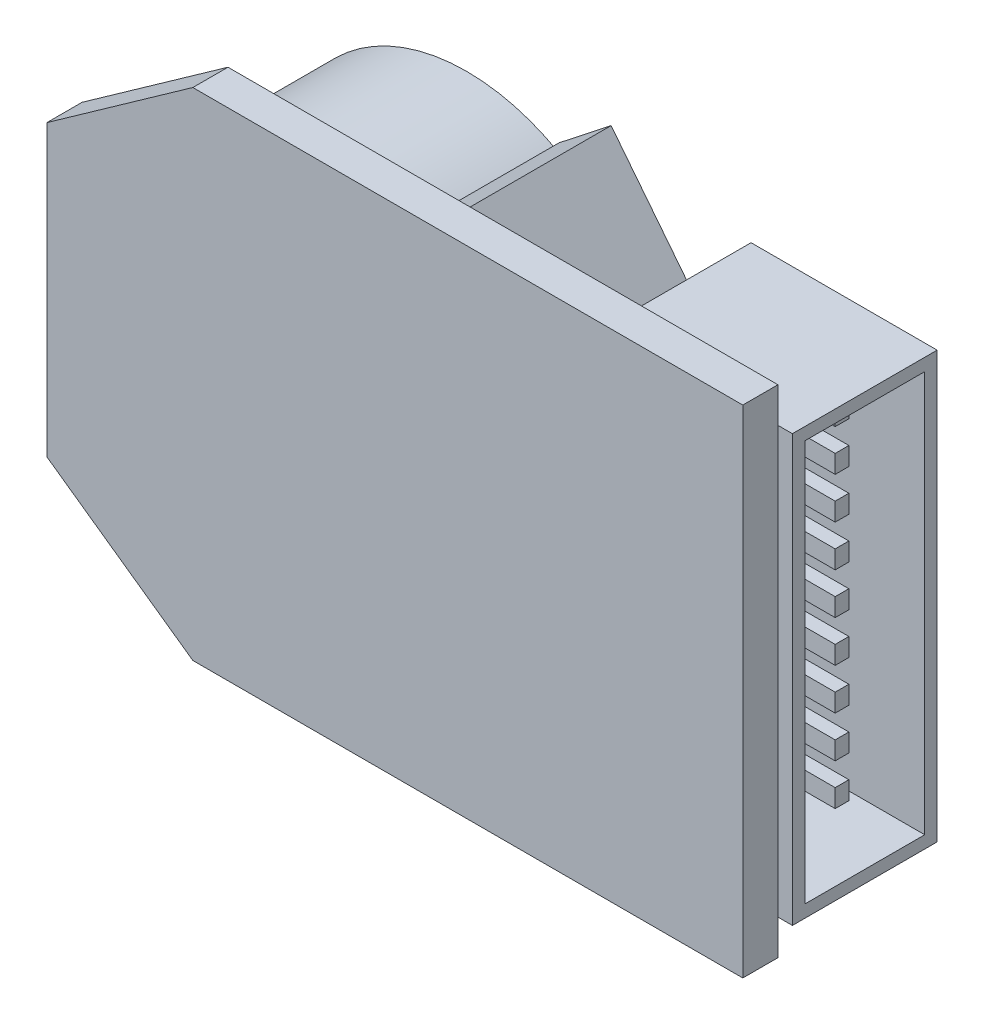
SolidWorks part; units mm, degrees
ref_plane "Alzado" through (0, 0, 0) normal (0, 0, 1) x (1, 0, 0)
ref_plane "Planta" through (0, 0, 0) normal (0, 1, 0) x (1, 0, 0)
ref_plane "Vista lateral" through (0, 0, 0) normal (1, 0, 0) x (0, 0, -1)
sketch "Croquis1" plane through (0, 0, 0) normal (0, 0, 1) x (1, 0, 0)
  line L0 (8.415, 6) -> (-4.885, 6)
  line L1 (-8.415, -6) -> (8.415, -6) construction
  line L2 (-8.415, -6) -> (-8.415, 6) construction
  line L3 (-8.415, 6) -> (8.415, 6) construction
  line L4 (8.415, -6) -> (8.415, 6)
  line L5 (-8.415, -6) -> (8.415, 6) construction
  line L6 (-8.415, 6) -> (8.415, -6) construction
  line L7 (0, 0) -> (-8.415, 0) construction
  line L8 (-8.415, -3.5) -> (-8.415, 3.5)
  line L9 (-8.415, 3.5) -> (-4.885, 6)
  line L10 (-8.415, -3.5) -> (-4.885, -6)
  line L11 (8.415, -6) -> (-4.885, -6)
  point P0 (0, 0)
  dimension "D1" = 16.83
  dimension "D2" = 12
  dimension "D3" = 13.3
  dimension "D4" = 3.5
extrude "Saliente-Extruir1" add sketch "Croquis1" along normal blind 0.85
ref_plane "Plano1" through (0, 0, -1) normal (0, 0, -1) x (-1, 0, 0)
sketch "Croquis2" plane through (0, 0, -1) normal (0, 0, -1) x (-1, 0, 0)
  circle A0 centre (3.415, 0) radius 0.85 construction
  circle A1 centre (3.415, 0) radius 0.85 construction
  circle A2 centre (3.415, 0) radius 0.7322
  circle A3 centre (3.415, 0) radius 4.5
  dimension "D1" = 9
extrude "Saliente-Extruir2" add sketch "Croquis2" along normal blind 3.3 separate body
sketch "Croquis3" plane through (0, 0, 0) normal (0, 0, -1) x (-1, 0, 0)
  line L0 (3.415, 0) -> (-1.5379, 3.8934) construction
  line L1 (-1.5379, 3.8934) -> (-2.7739, 2.3211) construction
  line L2 (-1.5379, 3.8934) -> (-0.3019, 5.4658) construction
  line L3 (-2.1668, 4.3878) -> (-0.9308, 5.9602)
  line L4 (-2.1668, 4.3878) -> (-3.4028, 2.8155)
  line L5 (-0.909, 3.399) -> (0.3271, 4.9714)
  line L6 (-0.909, 3.399) -> (-2.145, 1.8267)
  line L7 (-3.4028, 2.8155) -> (-2.145, 1.8267)
  line L8 (-0.9308, 5.9602) -> (0.3271, 4.9714)
  line L9 (3.415, 0) -> (-5.085, 0) construction
  line L10 (-0.9308, -5.9602) -> (0.3271, -4.9714)
  line L11 (-0.909, -3.399) -> (0.3271, -4.9714)
  line L12 (-0.909, -3.399) -> (-2.145, -1.8267)
  line L13 (-3.4028, -2.8155) -> (-2.145, -1.8267)
  line L14 (-2.1668, -4.3878) -> (-3.4028, -2.8155)
  line L15 (-2.1668, -4.3878) -> (-0.9308, -5.9602)
  dimension "D1" = 6.3
  dimension "D2" = 2
  dimension "D3" = 2
  dimension "D4" = 0.8
  dimension "D5" = 0.8
extrude "Saliente-Extruir3" add sketch "Croquis3" along normal blind 3.45
sketch "Croquis4" plane through (0, 0, 0) normal (0, 0, -1) x (-1, 0, 0)
  line L0 (-8.415, -6) -> (-8.415, 6) construction
  line L1 (-8.415, -6) -> (-8.415, 6) construction
  line L2 (-8.415, 0) -> (-4.265, 0) construction
  line L3 (-8.415, 0) -> (-8.765, 0) construction
  line L4 (-4.265, 5.15) -> (-4.265, -5.15)
  line L5 (-4.265, -5.15) -> (-8.765, -5.15)
  line L6 (-8.765, -5.15) -> (-8.765, 5.15)
  line L7 (-4.265, 5.15) -> (-8.765, 5.15)
  dimension "D1" = 4.15
  dimension "D2" = 0.35
  dimension "D3" = 5.15
extrude "Saliente-Extruir4" add sketch "Croquis4" along normal blind 3.5
sketch "Croquis5" plane through (8.765, 0, 0) normal (1, 0, 0) x (0, 0, -1)
  line L8 (0.3, 4.85) -> (0.3, -4.85)
  line L9 (0.3, -4.85) -> (3.2, -4.85)
  line L10 (3.2, -4.85) -> (3.2, 4.85)
  line L11 (3.2, 4.85) -> (0.3, 4.85)
  line L12 (0.3, 4.85) -> (0.3, -4.85)
  line L13 (0.3, -4.85) -> (3.2, -4.85)
  line L14 (3.2, -4.85) -> (3.2, 4.85)
  line L15 (3.2, 4.85) -> (0.3, 4.85)
  dimension "D1" = 0.3
extrude "Cortar-Extruir1" cut sketch "Croquis5" against normal blind 3
sketch "Croquis6" plane through (5.765, 0, 0) normal (1, 0, 0) x (0, 0, -1)
  line L0 (3.2, -4.85) -> (3.2, 4.85) construction
  line L1 (3.2, -4.85) -> (3.2, 4.85) construction
  line L2 (3.2, 0) -> (2.2, 0) construction
  line L3 (2.2, 0) -> (2.2, -3.1595) construction
  line L4 (2.0344, 0.22) -> (2.3656, 0.22)
  line L5 (2.0344, 0.22) -> (2.0344, -0.22)
  line L6 (2.0344, -0.22) -> (2.3656, -0.22)
  line L7 (2.3656, 0.22) -> (2.3656, -0.22)
  line L8 (2.0344, 0.22) -> (2.3656, -0.22) construction
  line L9 (2.0344, -0.22) -> (2.3656, 0.22) construction
  line L10 (2.3656, 1.22) -> (2.3656, 0.78)
  line L11 (2.0344, 1.22) -> (2.3656, 1.22)
  line L12 (2.0344, 1.22) -> (2.0344, 0.78)
  line L13 (2.0344, 0.78) -> (2.3656, 0.78)
  line L14 (2.3656, 2.22) -> (2.3656, 1.78)
  line L15 (2.0344, 2.22) -> (2.3656, 2.22)
  line L16 (2.0344, 2.22) -> (2.0344, 1.78)
  line L17 (2.0344, 1.78) -> (2.3656, 1.78)
  line L18 (2.3656, 3.22) -> (2.3656, 2.78)
  line L19 (2.0344, 3.22) -> (2.3656, 3.22)
  line L20 (2.0344, 3.22) -> (2.0344, 2.78)
  line L21 (2.0344, 2.78) -> (2.3656, 2.78)
  line L22 (2.3656, 4.22) -> (2.3656, 3.78)
  line L23 (2.0344, 4.22) -> (2.3656, 4.22)
  line L24 (2.0344, 4.22) -> (2.0344, 3.78)
  line L25 (2.0344, 3.78) -> (2.3656, 3.78)
  line L26 (2.3656, -0.78) -> (2.3656, -1.22)
  line L27 (2.0344, -0.78) -> (2.0344, -1.22)
  line L28 (2.0344, -0.78) -> (2.3656, -0.78)
  line L29 (2.0344, -1.22) -> (2.3656, -1.22)
  line L30 (2.3656, -1.78) -> (2.3656, -2.22)
  line L31 (2.0344, -1.78) -> (2.0344, -2.22)
  line L32 (2.0344, -1.78) -> (2.3656, -1.78)
  line L33 (2.0344, -2.22) -> (2.3656, -2.22)
  line L34 (2.3656, -2.78) -> (2.3656, -3.22)
  line L35 (2.0344, -2.78) -> (2.0344, -3.22)
  line L36 (2.0344, -2.78) -> (2.3656, -2.78)
  line L37 (2.0344, -3.22) -> (2.3656, -3.22)
  line L38 (2.3656, -3.78) -> (2.3656, -4.22)
  line L39 (2.0344, -3.78) -> (2.0344, -4.22)
  line L40 (2.0344, -3.78) -> (2.3656, -3.78)
  line L41 (2.0344, -4.22) -> (2.3656, -4.22)
  dimension "D1" = 1
  dimension "D2" = 0.44
  dimension "D3" = 5
  dimension "D4" = 5
extrude "Saliente-Extruir6" add sketch "Croquis6" along normal blind 2
